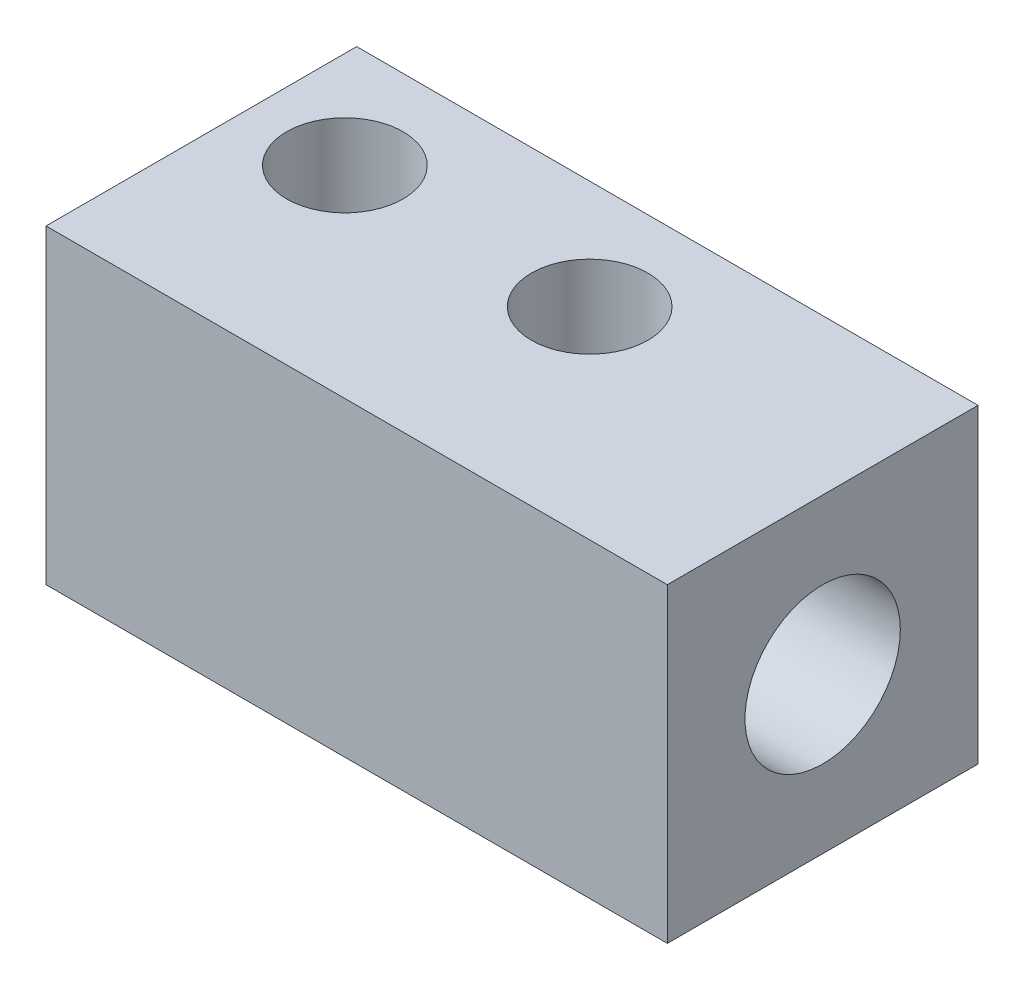
SolidWorks part; units mm, degrees
ref_plane "Front Plane" through (0, 0, 0) normal (0, 0, 1) x (1, 0, 0)
ref_plane "Top Plane" through (0, 0, 0) normal (0, 1, 0) x (1, 0, 0)
ref_plane "Right Plane" through (0, 0, 0) normal (1, 0, 0) x (0, 0, -1)
sketch "Sketch1" plane through (0, 0, 0) normal (0, 0, 1) x (1, 0, 0)
  line L1 (0, 0) -> (25.4, 0)
  line L2 (0, 0) -> (0, 12.7)
  line L3 (0, 12.7) -> (25.4, 12.7)
  line L4 (25.4, 0) -> (25.4, 12.7)
  dimension "D1" = 25.4
  dimension "D2" = 12.7
extrude "Boss-Extrude1" add sketch "Sketch1" along normal mid plane 12.7
hole_wizard "3/16 (0.1875) Dowel Hole1" positions "3DSketch2" profile "Sketch4" hole size "3/16" standard "ANSI Inch" end condition through all
sketch3d "3DSketch2"
  line L1 (25.4, 12.7, 6.35) -> (25.4, 12.7, -6.35) construction
  line L2 (25.4, 12.7, -6.35) -> (0, 12.7, -6.35) construction
  point P2 (13.97, 12.7, -1.905)
  point P4 (3.9624, 12.7, -1.905)
  dimension "D1" = 10.0076
  dimension "D2" = 11.43
  dimension "D3" = 4.445
sketch "Sketch4" plane through (13.97, 12.7, -1.905) normal (1, 0, 0) x (0, 0, 1)
  line L0 (0, 0) -> (0, 12.7)
  line L1 (0, 12.7) -> (2.3812, 12.7)
  line L2 (2.3812, 12.7) -> (2.3812, 0)
  line L5 (2.3812, 0) -> (0, 0)
  line L11 (0, -6.35) -> (0, 107.95) construction
  dimension "Thru Hole Dia." = 4.7625
  dimension "Thru Hole Depth" = 12.7
sketch "Sketch6" plane through (25.4, 0, 0) normal (1, 0, 0) x (0, 0, -1)
  line L1 (-6.35, 0) -> (6.35, 0) construction
  line L2 (-6.35, 0) -> (-6.35, 12.7) construction
  circle A0 centre (0, 6.35) radius 3.175
  point P2 (0, 0)
  point P7 (-6.35, 6.35)
  dimension "D1" = 6.35
extrude "Cut-Extrude1" cut sketch "Sketch6" against normal blind 6.35
